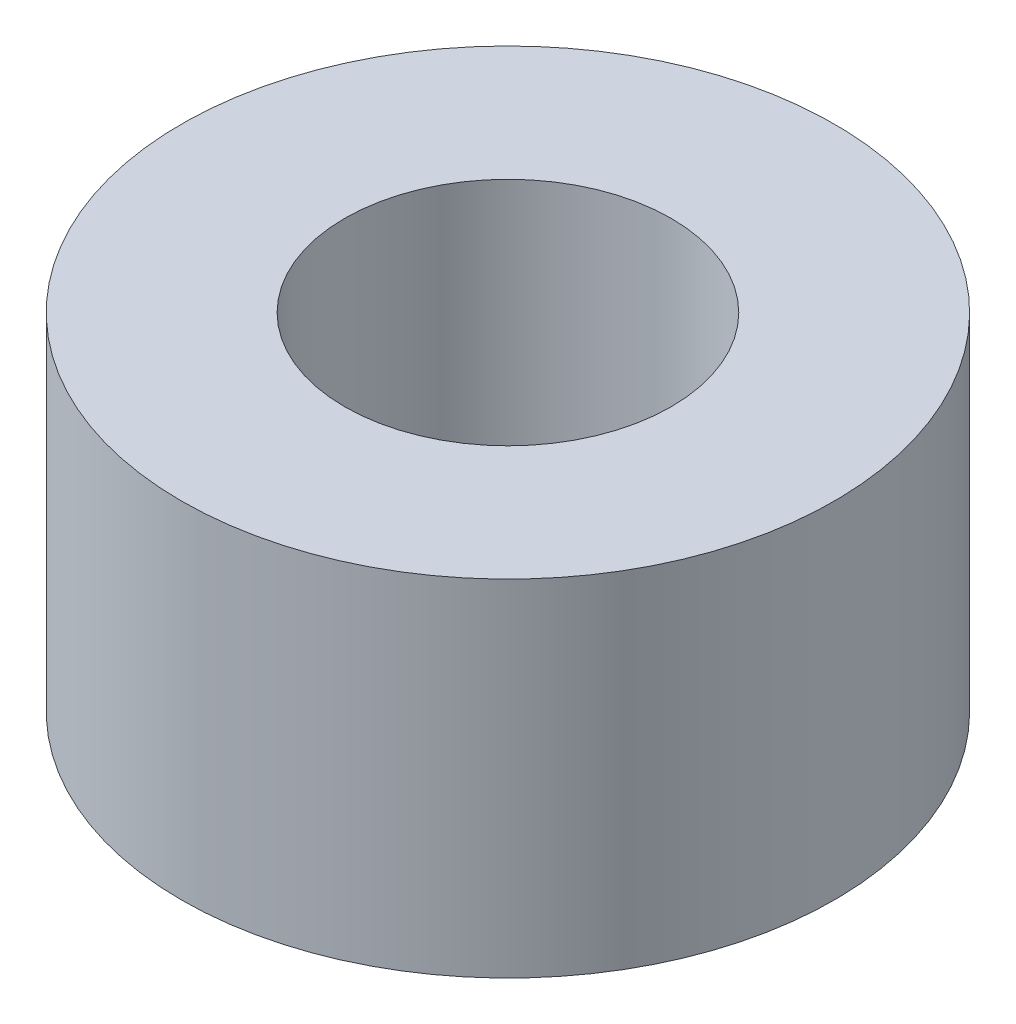
SolidWorks part; units mm, degrees
material "Acrylic (Medium-high impact)"
ref_plane "Front Plane" through (0, 0, 0) normal (0, 0, 1) x (1, 0, 0)
ref_plane "Top Plane" through (0, 0, 0) normal (0, 1, 0) x (1, 0, 0)
ref_plane "Right Plane" through (0, 0, 0) normal (1, 0, 0) x (0, 0, -1)
sketch "Sketch1" plane through (0, 0, 0) normal (0, 1, 0) x (1, 0, 0)
  circle A0 centre (0, 0) radius 3
  circle A1 centre (0, 0) radius 6
  dimension "D1" = 12
  dimension "D2" = 6
extrude "Boss-Extrude1" add sketch "Sketch1" along normal mid plane 6.35
